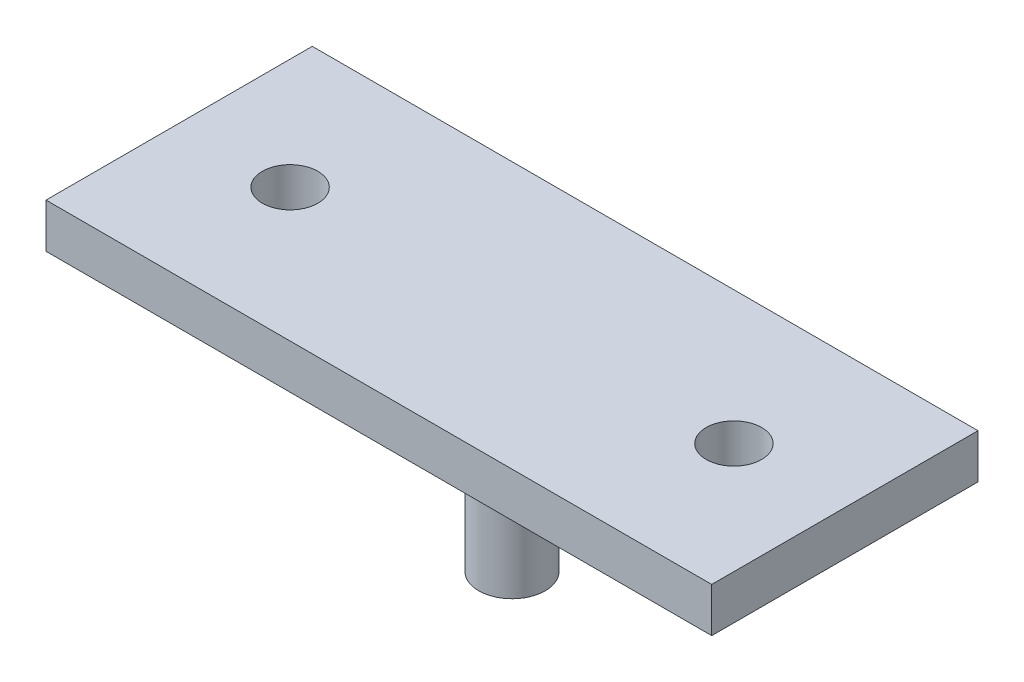
SolidWorks part; units mm, degrees
ref_plane "Front Plane" through (0, 0, 0) normal (0, 0, 1) x (1, 0, 0)
ref_plane "Top Plane" through (0, 0, 0) normal (0, 1, 0) x (1, 0, 0)
ref_plane "Right Plane" through (0, 0, 0) normal (1, 0, 0) x (0, 0, -1)
sketch "Sketch2" plane through (0, 0, 0) normal (0, 1, 0) x (1, 0, 0)
  line L0 (-19.05, 0) -> (19.05, 0) construction
  line L1 (-19.05, -7.62) -> (19.05, -7.62)
  line L2 (-19.05, -7.62) -> (-19.05, 7.62)
  line L3 (-19.05, 7.62) -> (19.05, 7.62)
  line L4 (19.05, -7.62) -> (19.05, 7.62)
  line L5 (-19.05, -7.62) -> (19.05, 7.62) construction
  line L6 (-19.05, 7.62) -> (19.05, -7.62) construction
  line L7 (0, 7.62) -> (0, -7.62) construction
  circle A0 centre (12.7, 0) radius 1.5875
  circle A1 centre (-12.7, 0) radius 1.5875
  point P0 (0, 0)
  dimension "D4" = 3.175
  dimension "D1" = 38.1
  dimension "D2" = 15.24
  dimension "D3" = 25.4
extrude "Boss-Extrude1" add sketch "Sketch2" along normal blind 2.54
sketch "Sketch3" plane through (0, 0, 0) normal (0, -1, 0) x (1, 0, 0)
  circle A0 centre (0, 0) radius 1.905
  dimension "D1" = 3.81
extrude "Boss-Extrude2" add sketch "Sketch3" along normal blind 10.16
